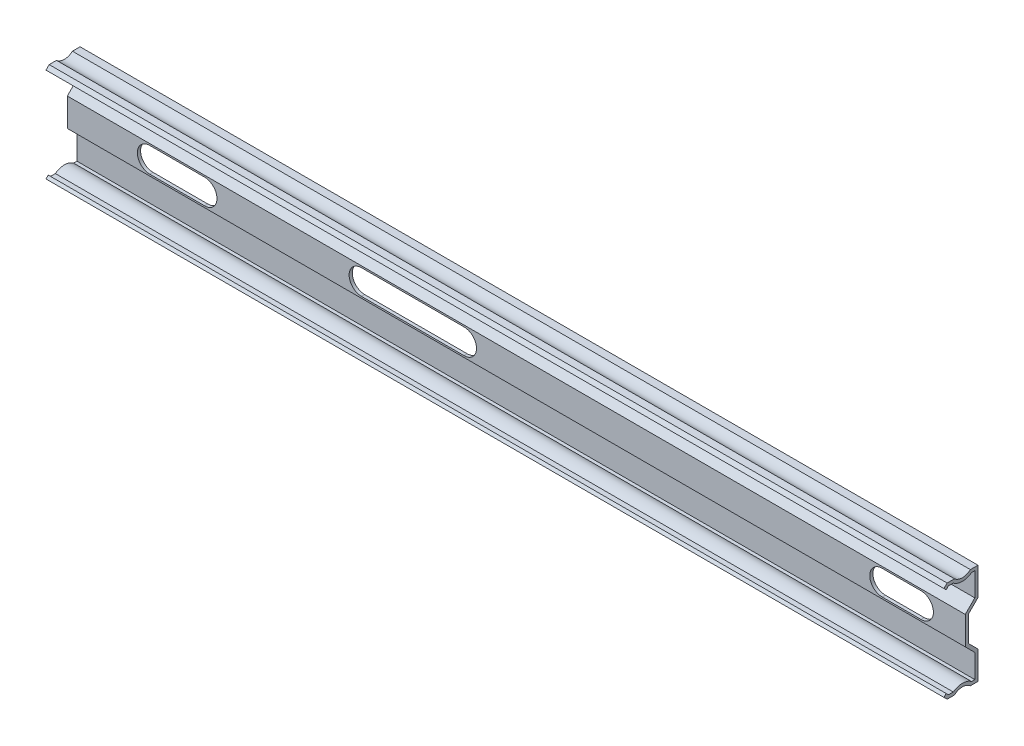
SolidWorks part; units mm, degrees
ref_plane "Front Plane" through (0, 0, 0) normal (0, 0, 1) x (1, 0, 0)
ref_plane "Top Plane" through (0, 0, 0) normal (0, 1, 0) x (1, 0, 0)
ref_plane "Right Plane" through (0, 0, 0) normal (1, 0, 0) x (0, 0, -1)
sketch "Sketch1" plane through (0, 0, 0) normal (1, 0, 0) x (0, 0, -1)
  line L0 (0, -22.85) -> (0, 22.85) construction
  line L1 (0, 22.85) -> (-12.7, 22.85) construction
  line L2 (-12.7, 22.85) -> (-12.7, 17.562) construction
  line L4 (0, -22.85) -> (-12.7, -22.85) construction
  line L5 (-12.7, -22.85) -> (-12.7, -17.562) construction
  line L6 (-12.7, 14.8049) -> (-11.7, 15.8049)
  line L7 (-11.7, 15.8049) -> (-9.4011, 15.8049)
  line L8 (-2, 15.8049) -> (-2, 7)
  line L9 (-2, 7) -> (-5, 4)
  line L10 (-5, 4) -> (-5, -4)
  line L11 (-5, -4) -> (-2, -7)
  line L12 (-2, -7) -> (-2, -15.8049)
  line L13 (-2, -15.8049) -> (-4.4011, -15.8049)
  line L14 (-11.7, -15.8049) -> (-12.7, -14.8049)
  line L15 (-4.4011, 15.8049) -> (-2, 15.8049)
  line L16 (-1, -22.85) -> (-1, 21.85) construction
  line L17 (-1, 21.85) -> (-11.7, 21.85) construction
  line L18 (-11.7, 21.85) -> (-11.7, 17.562) construction
  line L19 (0, 0) -> (-50000, 0) construction
  line L20 (-5, 0) -> (0, 0) construction
  line L21 (-9.4011, -15.8049) -> (-11.7, -15.8049)
  arc A1 (-9.4011, 15.8049) -> (-4.4011, 15.8049) centre (-6.9011, 18.6) ccw
  circle A2 centre (-6.9011, 18.6) radius 3.25 construction
  arc A3 (-9.4011, -15.8049) -> (-4.4011, -15.8049) centre (-6.9011, -18.6) cw
  circle A4 centre (-6.9011, -18.6) radius 3.25 construction
  point P4 (0, 0)
  dimension "D3" = 6.5
  dimension "D4" = 0.5
  dimension "D1" = 45.7
  dimension "D2" = 12.7
  dimension "D5" = 1
  dimension "D6" = 5
  dimension "D7" = 2
  dimension "D9" = 3
  dimension "D10" = 8
  dimension "D8" = 1
extrude "Extrude-Thin1" add sketch "Sketch1" against normal blind 282 thin contours L6 L7 A1 L15 L8 L9 L10 L11 L12 L13 A3 L21 L14
sketch "Esboço1" plane through (0, 0, 6) normal (0, 0, 1) x (1, 0, 0)
  line L0 (-13.9, 0) -> (-26.1, 0) construction
  line L1 (-13.9, -3.9) -> (-26.1, -3.9)
  line L2 (-13.9, 3.9) -> (-26.1, 3.9)
  line L4 (-189.6, 0) -> (-157.4, 0) construction
  line L5 (-189.6, 3.9) -> (-157.4, 3.9)
  line L6 (-189.6, -3.9) -> (-157.4, -3.9)
  line L7 (-256.1, 0) -> (-238.9, 0) construction
  line L8 (-256.1, 3.9) -> (-238.9, 3.9)
  line L9 (-256.1, -3.9) -> (-238.9, -3.9)
  line L10 (-282, 4.4142) -> (-282, -4.4142) construction
  arc A0 (-13.9, -3.9) -> (-13.9, 3.9) centre (-13.9, 0) ccw
  arc A1 (-26.1, 3.9) -> (-26.1, -3.9) centre (-26.1, 0) ccw
  arc A2 (-189.6, 3.9) -> (-189.6, -3.9) centre (-189.6, 0) ccw
  arc A3 (-157.4, -3.9) -> (-157.4, 3.9) centre (-157.4, 0) ccw
  arc A4 (-256.1, 3.9) -> (-256.1, -3.9) centre (-256.1, 0) ccw
  arc A5 (-238.9, -3.9) -> (-238.9, 3.9) centre (-238.9, 0) ccw
  point P3 (-20, 0)
  point P8 (-10, 0)
  point P9 (-30, 0)
  point P12 (-173.5, 0)
  point P17 (-153.5, 0)
  point P18 (-193.5, 0)
  point P21 (-247.5, 0)
  point P26 (-260, 0)
  point P27 (-235, 0)
  dimension "D1" = 7.8
  dimension "D2" = 20
  dimension "D3" = 10
  dimension "D4" = 7.8
  dimension "D5" = 40
  dimension "D6" = 123.5
  dimension "D7" = 7.8
  dimension "D8" = 25
  dimension "D9" = 22
extrude "Corte-extrusão1" cut sketch "Esboço1" against normal through all
